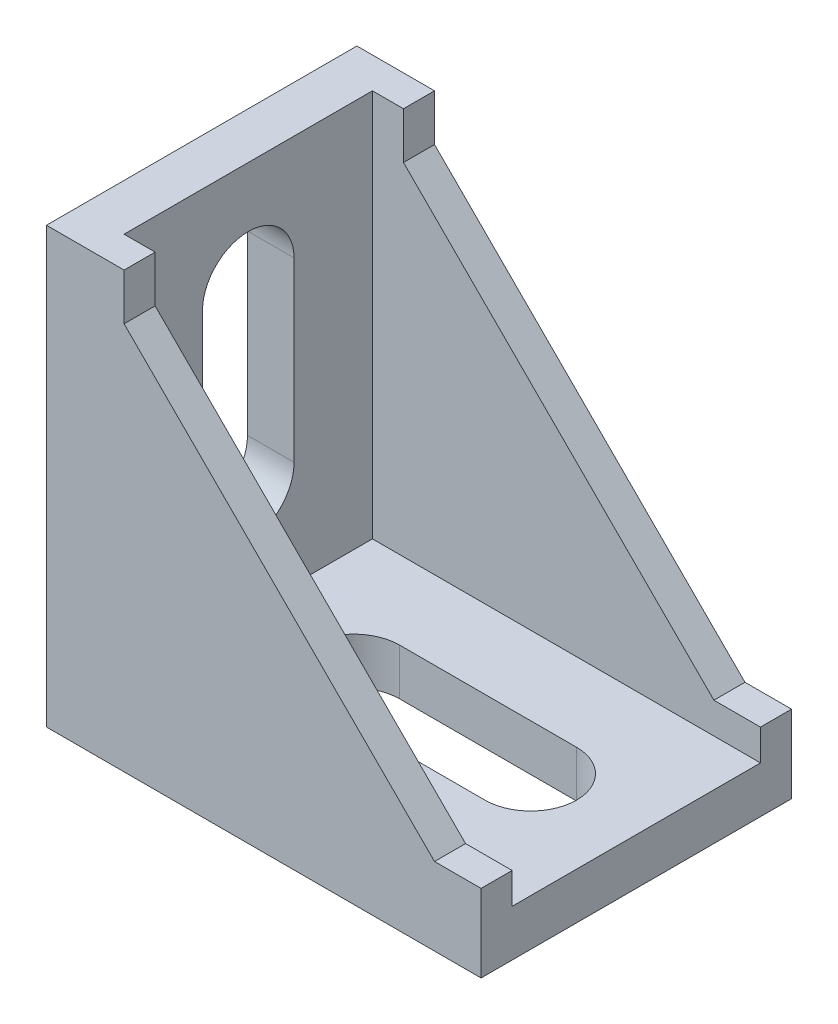
SolidWorks part; units mm, degrees
ref_plane "Front Plane" through (0, 0, 0) normal (0, 0, 1) x (1, 0, 0)
ref_plane "Top Plane" through (0, 0, 0) normal (0, 1, 0) x (1, 0, 0)
ref_plane "Right Plane" through (0, 0, 0) normal (1, 0, 0) x (0, 0, -1)
sketch "Sketch2" plane through (0, 0, 0) normal (0, 0, 1) x (1, 0, 0)
  line L0 (0, 0) -> (0, 28)
  line L1 (0, 28) -> (3, 28)
  line L2 (3, 28) -> (3, 3)
  line L3 (3, 3) -> (28, 3)
  line L4 (28, 3) -> (28, 0)
  line L5 (28, 0) -> (0, 0)
  dimension "D1" = 28
  dimension "D2" = 3
extrude "Boss-Extrude1" add sketch "Sketch2" against normal blind 20
sketch "Sketch4" plane through (0, 3, 0) normal (0, 1, 0) x (1, 0, 0)
  line L0 (0, 10) -> (28, 10) construction
  line L1 (0, 20) -> (0, 0) construction
  line L2 (28, 20) -> (28, 0) construction
  line L3 (15.5, 20) -> (15.5, 0) construction
  line L4 (28, 20) -> (3, 20) construction
  line L5 (28, 0) -> (3, 0) construction
  line L6 (9.8, 10) -> (21.2, 10) construction
  line L7 (9.8, 12.95) -> (21.2, 12.95)
  line L8 (9.8, 7.05) -> (21.2, 7.05)
  arc A0 (9.8, 12.95) -> (9.8, 7.05) centre (9.8, 10) ccw
  arc A1 (21.2, 7.05) -> (21.2, 12.95) centre (21.2, 10) ccw
  point P14 (15.5, 10)
  point P19 (0, 0)
  dimension "D1" = 11.4
  dimension "D2" = 5.9
extrude "Cut-Extrude1" cut sketch "Sketch4" against normal blind 10
sketch "Sketch5" plane through (3, 0, 0) normal (1, 0, 0) x (0, 0, -1)
  line L0 (10, 28) -> (10, 0) construction
  line L1 (20, 28) -> (0, 28) construction
  line L2 (20, 0) -> (0, 0) construction
  line L3 (0, 15.5) -> (20, 15.5) construction
  line L4 (0, 3) -> (0, 28) construction
  line L5 (20, 3) -> (20, 28) construction
  line L6 (10, 21.2) -> (10, 9.8) construction
  line L7 (12.95, 21.2) -> (12.95, 9.8)
  line L8 (7.05, 21.2) -> (7.05, 9.8)
  arc A0 (12.95, 21.2) -> (7.05, 21.2) centre (10, 21.2) ccw
  arc A1 (7.05, 9.8) -> (12.95, 9.8) centre (10, 9.8) ccw
  point P14 (10, 15.5)
  point P19 (0, 0)
  dimension "D1" = 5.9
  dimension "D2" = 11.4
extrude "Cut-Extrude2" cut sketch "Sketch5" against normal blind 10
sketch "Sketch6" plane through (0, 0, 0) normal (0, 0, 1) x (1, 0, 0)
  line L0 (3, 28) -> (5, 28)
  line L1 (5, 28) -> (5, 25)
  line L2 (5, 25) -> (25, 5)
  line L3 (25, 5) -> (28, 5)
  line L4 (28, 5) -> (28, 3)
  line L5 (3, 3) -> (3, 28) construction
  line L6 (28, 3) -> (3, 3) construction
  line L7 (3, 28) -> (3, 3)
  line L8 (3, 3) -> (28, 3)
  dimension "D1" = 2
  dimension "D2" = 2
  dimension "D3" = 135
  dimension "D4" = 20
extrude "Boss-Extrude2" add sketch "Sketch6" against normal blind 2
ref_plane "Plane1" through (0, 0, -10) normal (0, 0, -1) x (-1, 0, 0)
mirror "Mirror4" about plane through (0, 0, -10) normal (0, 0, -1) of "Boss-Extrude2"
